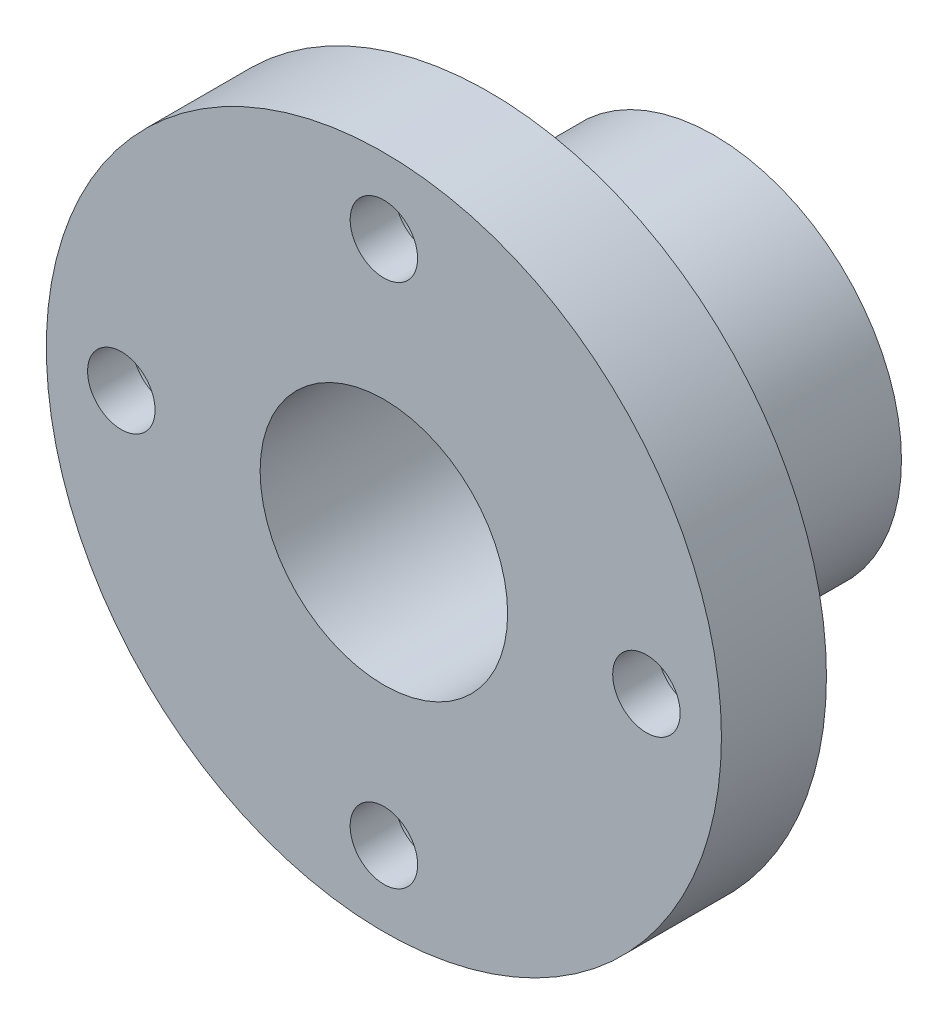
SolidWorks part; units mm, degrees
ref_plane "前视基准面" through (0, 0, 0) normal (0, 0, 1) x (1, 0, 0)
ref_plane "上视基准面" through (0, 0, 0) normal (0, 1, 0) x (1, 0, 0)
ref_plane "右视基准面" through (0, 0, 0) normal (1, 0, 0) x (0, 0, -1)
sketch "草图1" plane through (0, 0, 0) normal (0, 0, 1) x (1, 0, 0)
  circle A0 centre (0, 0) radius 12.5
  dimension "D1" = 25
extrude "拉伸1" add sketch "草图1" along normal blind 15
sketch "草图2" plane through (0, 0, 15) normal (0, 0, 1) x (1, 0, 0)
  circle A0 centre (0, 0) radius 22.5
  dimension "D1" = 45
extrude "拉伸2" add sketch "草图2" along normal blind 7
hole_wizard "M18x1.5 螺纹孔1" positions "草图4" profile "草图3" tap size "M18x1.5" standard "GB"
sketch "草图4" plane through (0, 0, 0) normal (0, 0, -1) x (-1, 0, 0)
  circle A0 centre (0, 0) radius 12.5 construction
  point P0 (0, 0)
sketch "草图3" plane through (0, 0, 0) normal (1, 0, 0) x (0, 1, 0)
  line L0 (0, 0) -> (0, 48.4571)
  line L1 (0, 48.4571) -> (8.25, 43.5)
  line L2 (8.25, 43.5) -> (8.25, 0)
  line L5 (8.25, 0) -> (0, 0)
  line L10 (0, 48.4571) -> (-8.25, 43.5) construction
  line L11 (0, -6.35) -> (0, 107.95) construction
  dimension "螺纹孔钻头直径" = 16.5
  dimension "螺纹孔钻头深度" = 43.5
  dimension "导头角度" = 118
cosmetic thread "孔螺蚊线1" parameters "D1"=20, "D2"=18
hole_wizard "M4 六角凹头螺钉的柱形沉头孔1" positions "草图6" profile "草图5" counterbore size "M4" standard "ISO" end condition through all
sketch "草图6" plane through (0, 0, 15) normal (0, 0, -1) x (-1, 0, 0)
  circle A0 centre (0, 0) radius 17.5 construction
  point P0 (0, 17.5)
  dimension "D1" = 35
sketch "草图5" plane through (0, 17.5, 15) normal (1, 0, 0) x (0, 1, 0)
  line L0 (0, 0) -> (0, 7)
  line L1 (0, 7) -> (2.25, 7)
  line L3 (2.25, 7) -> (2.25, 4)
  line L4 (4, 4) -> (2.25, 4)
  line L5 (4, 4) -> (4, 0.025)
  line L6 (4, 0.025) -> (4.025, 0)
  line L7 (4.025, 0) -> (0, 0)
  line L8 (-4, 0.025) -> (-4.025, 0) construction
  line L11 (0, -6.35) -> (0, 107.95) construction
  dimension "通孔孔直径" = 4.5
  dimension "通孔孔深度" = 7
  dimension "柱形沉头孔直径" = 8
  dimension "柱形沉头孔深度" = 4
  dimension "近端锥形沉头孔直径" = 8.05
  dimension "近端锥形沉头孔角度" = 90
pattern_circular "阵列(圆周)1" count 4 over 360 about axis through (0, 0, 0) along (0, 0, 1) of "M4 六角凹头螺钉的柱形沉头孔1"
